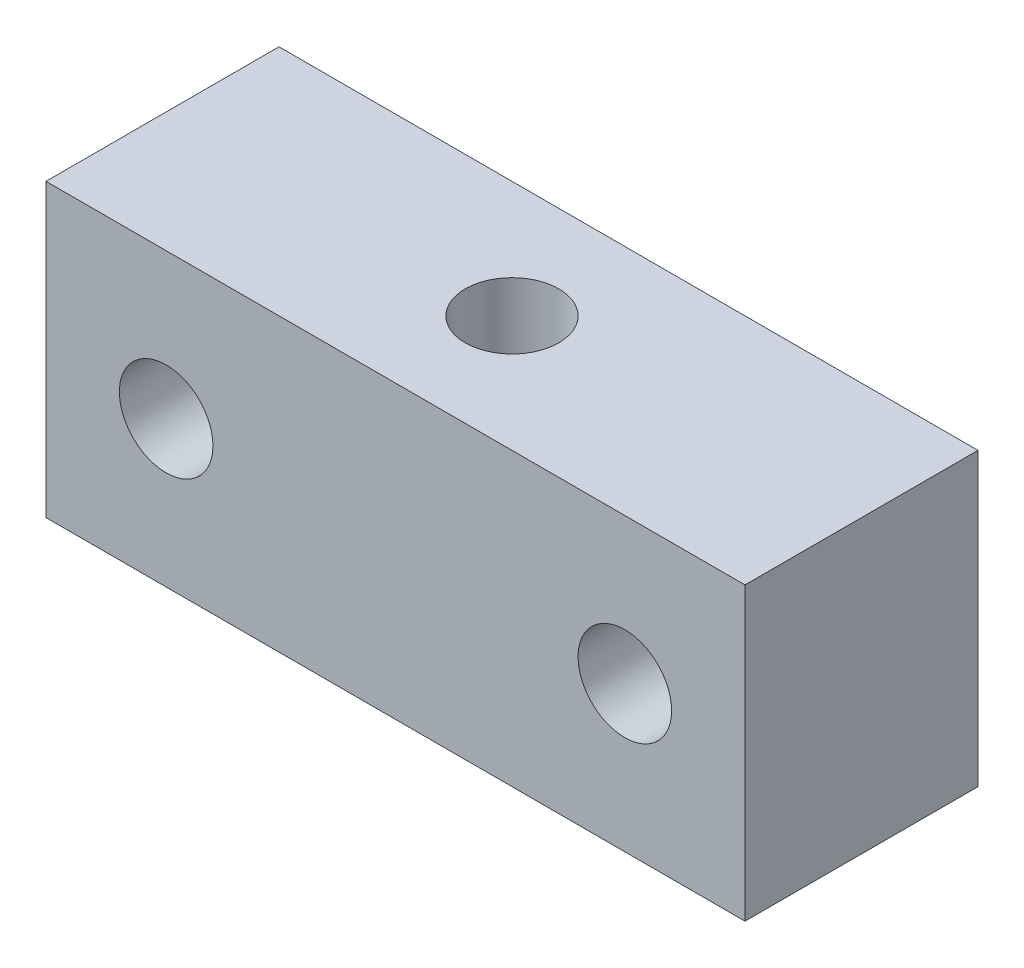
SolidWorks part; units mm, degrees
material "Plain Carbon Steel"
ref_plane "Front Plane" through (0, 0, 0) normal (0, 0, 1) x (1, 0, 0)
ref_plane "Top Plane" through (0, 0, 0) normal (0, 1, 0) x (1, 0, 0)
ref_plane "Right Plane" through (0, 0, 0) normal (1, 0, 0) x (0, 0, -1)
sketch "Sketch1" plane through (0, 0, 0) normal (0, 0, 1) x (1, 0, 0)
  line L1 (0, 0) -> (76.2, 0)
  line L2 (0, 0) -> (0, 31.75)
  line L3 (0, 31.75) -> (76.2, 31.75)
  line L4 (76.2, 0) -> (76.2, 31.75)
  dimension "D1" = 31.75
  dimension "D2" = 76.2
extrude "Boss-Extrude1" add sketch "Sketch1" along normal blind 25.4
hole_wizard "M12 Tapped Hole2" positions "Sketch3" profile "Sketch2" tap size "M12" standard "Peddi DIN" end condition through all
sketch "Sketch3" plane through (0, 0, 25.4) normal (0, 0, 1) x (1, 0, 0)
  line L0 (38.1, 31.75) -> (38.1, 15.875) construction
  line L1 (76.2, 31.75) -> (0, 31.75) construction
  line L2 (38.1, 15.875) -> (38.1, 0) construction
  line L3 (0, 0) -> (76.2, 0) construction
  line L6 (13.1, 15.875) -> (63.1, 15.875) construction
  point P12 (13.1, 15.875)
  point P13 (63.1, 15.875)
  dimension "D1" = 50
sketch "Sketch2" plane through (13.1, 15.875, 25.4) normal (1, 0, 0) x (0, -1, 0)
  line L0 (0, 0) -> (0, 25.4)
  line L1 (0, 25.4) -> (5.1, 25.4)
  line L2 (5.1, 25.4) -> (5.1, 0)
  line L5 (5.1, 0) -> (0, 0)
  line L11 (0, -6.35) -> (0, 107.95) construction
  dimension "Thru Tap Drill Dia." = 10.2
  dimension "Thru Tap Drill Depth" = 25.4
cosmetic thread "Hole Thread2"
cosmetic thread "Hole Thread3"
hole_wizard "M12 Tapped Hole1" positions "Sketch5" profile "Sketch4" tap size "M12" standard "Peddi DIN" end condition through all
sketch "Sketch5" plane through (0, 31.75, 0) normal (0, 1, 0) x (1, 0, 0)
  line L0 (76.2, 0) -> (0, 0) construction
  line L4 (38.1, 0) -> (38.1, -25.4) construction
  line L5 (76.2, -25.4) -> (0, -25.4) construction
  point P0 (38.1, -12.7)
  dimension "D1" = 12.7
cosmetic thread "Hole Thread1" parameters "D2"=12
sketch "Sketch4" plane through (38.1, 31.75, 12.7) normal (1, 0, 0) x (0, 0, 1)
  line L0 (0, 0) -> (0, 31.75)
  line L1 (0, 31.75) -> (5.1, 31.75)
  line L2 (5.1, 31.75) -> (5.1, 0)
  line L5 (5.1, 0) -> (0, 0)
  line L11 (0, -6.35) -> (0, 107.95) construction
  dimension "Thru Tap Drill Dia." = 10.2
  dimension "Thru Tap Drill Depth" = 31.75
other "Freeze***"
